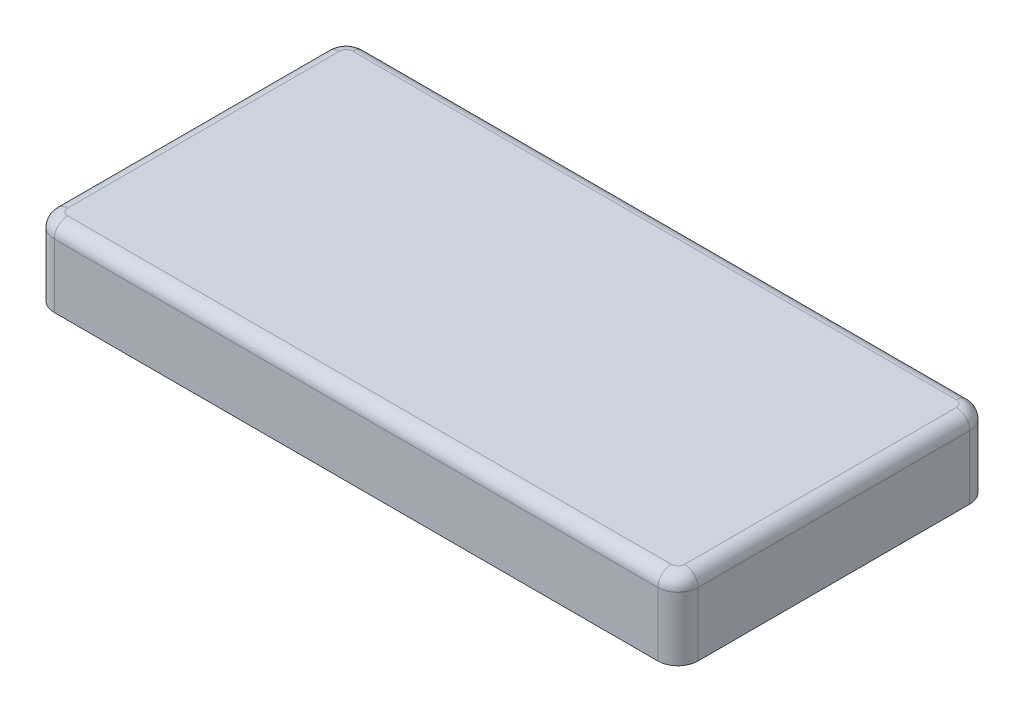
SolidWorks part; units mm, degrees
ref_plane "前视基准面" through (0, 0, 0) normal (0, 0, 1) x (1, 0, 0)
ref_plane "上视基准面" through (0, 0, 0) normal (0, 1, 0) x (1, 0, 0)
ref_plane "右视基准面" through (0, 0, 0) normal (1, 0, 0) x (0, 0, -1)
sketch "Sketch1" plane through (0, 1.6, 0) normal (0, 1, 0) x (1, 0, 0)
  circle A0 centre (-41.5925, 16.8275) radius 3.5
  circle A1 centre (-41.5925, -16.8275) radius 3.5
  circle A2 centre (41.5925, -16.8275) radius 3.5
  circle A3 centre (41.5925, 16.8275) radius 3.5
  dimension "D1" = 7
extrude "Boss-Extrude1" add sketch "Sketch1" along normal blind 5
sketch "Sketch2" plane through (0, 6.6, 0) normal (0, 1, 0) x (1, 0, 0)
  line L0 (-46.0375, 21.2725) -> (-46.0375, -21.2725) construction
  line L1 (-48.0375, 23.2725) -> (48.0375, 23.2725)
  line L2 (-48.0375, 23.2725) -> (-48.0375, -23.2725)
  line L3 (-48.0375, -23.2725) -> (48.0375, -23.2725)
  line L4 (48.0375, 23.2725) -> (48.0375, -23.2725)
  line L5 (-48.0375, 23.2725) -> (48.0375, -23.2725) construction
  line L6 (-48.0375, -23.2725) -> (48.0375, 23.2725) construction
  line L7 (46.0375, 21.2725) -> (-46.0375, 21.2725) construction
  point P0 (0, 0)
  dimension "D1" = 2
  dimension "D2" = 2
extrude "Boss-Extrude3" add sketch "Sketch2" against normal blind 1.5
sketch "Sketch3" plane through (0, 5.1, 0) normal (0, -1, 0) x (1, 0, 0)
  line L4 (48.0375, -23.2725) -> (48.0375, 23.2725)
  line L5 (48.0375, 23.2725) -> (-48.0375, 23.2725)
  line L6 (-48.0375, 23.2725) -> (-48.0375, -23.2725)
  line L7 (-48.0375, -23.2725) -> (48.0375, -23.2725)
  line L8 (48.0375, -23.2725) -> (48.0375, 23.2725)
  line L9 (48.0375, 23.2725) -> (-48.0375, 23.2725)
  line L10 (-48.0375, 23.2725) -> (-48.0375, -23.2725)
  line L11 (-48.0375, -23.2725) -> (48.0375, -23.2725)
  line L16 (46.5375, -21.7725) -> (46.5375, 21.7725)
  line L17 (46.5375, 21.7725) -> (-46.5375, 21.7725)
  line L18 (-46.5375, 21.7725) -> (-46.5375, -21.7725)
  line L19 (-46.5375, -21.7725) -> (46.5375, -21.7725)
  line L20 (46.5375, -21.7725) -> (46.5375, 21.7725)
  line L21 (46.5375, 21.7725) -> (-46.5375, 21.7725)
  line L22 (-46.5375, 21.7725) -> (-46.5375, -21.7725)
  line L23 (-46.5375, -21.7725) -> (46.5375, -21.7725)
  dimension "D1" = 0
  dimension "D2" = 1.5
extrude "Boss-Extrude4" add sketch "Sketch3" along normal blind 10
fillet "Fillet1" radius 3 4 edges at (48.0375, 0.85, -23.2725) (-48.0375, 0.85, -23.2725) (-48.0375, 0.85, 23.2725) (48.0375, 0.85, 23.2725)
fillet "Fillet2" radius 1.5 4 edges at (-46.5375, 0.1, -21.7725) (-46.5375, 0.1, 21.7725) (46.5375, 0.1, -21.7725) (46.5375, 0.1, 21.7725)
fillet "Fillet3" radius 2 8 edges at (-47.1588, 6.6, 22.3938) (-48.0375, 6.6, 0) (-47.1588, 6.6, -22.3938) (0, 6.6, -23.2725) (47.1588, 6.6, -22.3938) (48.0375, 6.6, 0) (47.1588, 6.6, 22.3938) (0, 6.6, 23.2725)
fillet "Fillet4" radius 0.5 8 edges at (46.0982, 5.1, 21.3332) (46.5375, 5.1, 0) (46.0982, 5.1, -21.3332) (0, 5.1, -21.7725) (-46.0982, 5.1, -21.3332) (-46.5375, 5.1, 0) (-46.0982, 5.1, 21.3332) (0, 5.1, 21.7725)
